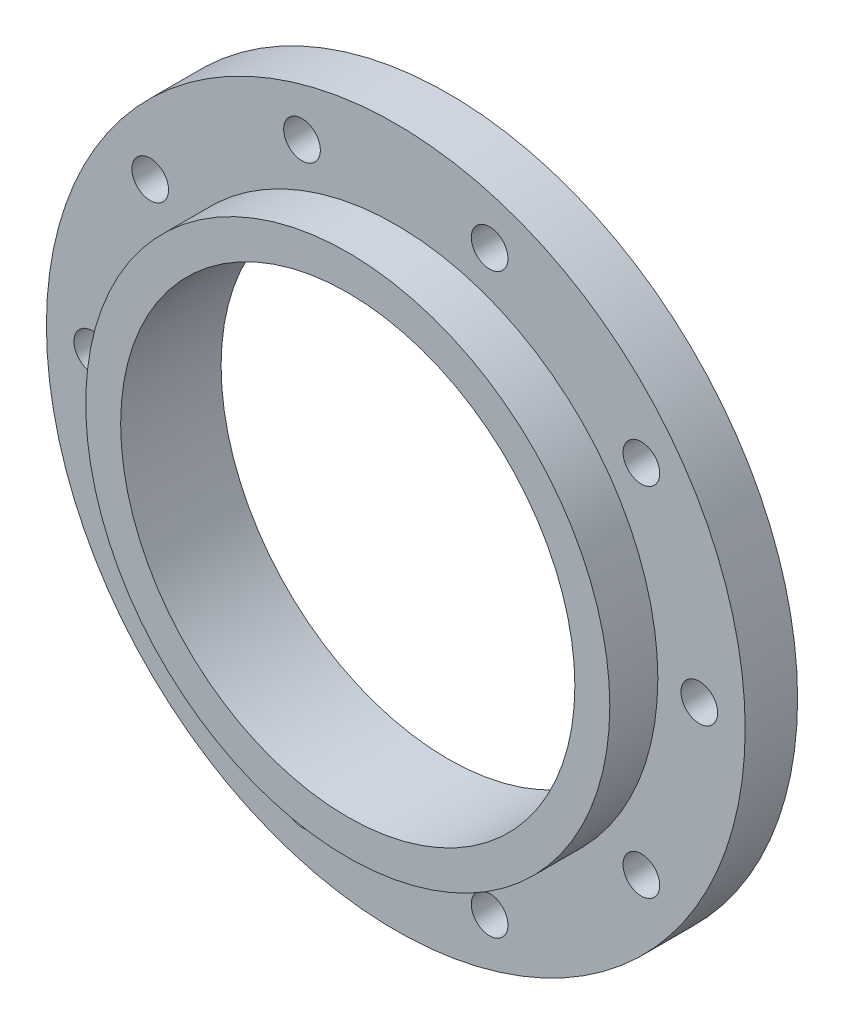
SolidWorks part; units mm, degrees
ref_plane "Front Plane" through (0, 0, 0) normal (0, 0, 1) x (1, 0, 0)
ref_plane "Top Plane" through (0, 0, 0) normal (0, 1, 0) x (1, 0, 0)
ref_plane "Right Plane" through (0, 0, 0) normal (1, 0, 0) x (0, 0, -1)
ref_plane "Plane1" through (0, 0, 0) normal (0, -1, 0) x (1, 0, 0)
sketch "Sketch1" plane through (0, 0, 0) normal (0, -1, 0) x (1, 0, 0)
  line L0 (80, 0) -> (0, 0)
  line L1 (0, 0) -> (0, -12)
  line L2 (0, -12) -> (80, -12)
  line L3 (80, -12) -> (80, 0)
  line L4 (0, 0) -> (0, -12) construction
revolve "Revolve1" add sketch "Sketch1" angle 360 about L4
sketch "Sketch2" plane through (0, 0, 0) normal (0, 0, 1) x (1, 0, 0)
  circle A0 centre (0, 0) radius 60
extrude "Boss-Extrude1" add sketch "Sketch2" along normal blind 11
hole_wizard "Ø8.4 (8.4) Diameter Hole1" positions "Sketch4" profile "Sketch3" hole size "Ø8.4" standard "ANSI Metric"
sketch "Sketch4" plane through (0, 0, -12) normal (0, 0, -1) x (-1, 0, 0)
  point P0 (21.4767, 66.0984)
  point P1 (56.2267, 40.8511)
  point P2 (69.5, 0)
  point P3 (56.2267, -40.8511)
  point P4 (21.4767, -66.0984)
  point P5 (-21.4767, -66.0984)
  point P6 (-56.2267, -40.8511)
  point P7 (-69.5, 0)
  point P8 (-56.2267, 40.8511)
  point P9 (-21.4767, 66.0984)
sketch "Sketch3" plane through (-21.4767, 66.0984, -12) normal (1, 0, 0) x (0, 1, 0)
  line L0 (0, 0) -> (0, 23)
  line L1 (0, 23) -> (4.2, 23)
  line L2 (4.2, 23) -> (4.2, 0)
  line L5 (4.2, 0) -> (0, 0)
  line L11 (0, -6.35) -> (0, 107.95) construction
  dimension "Thru Hole Dia." = 8.4
  dimension "Thru Hole Depth" = 23
hole_wizard "M100 Clearance Hole1" positions "Sketch6" profile "Sketch5" hole size "M100" standard "ANSI Metric"
sketch "Sketch6" plane through (0, 0, -12) normal (0, 0, -1) x (-1, 0, 0)
  point P0 (0, 0)
sketch "Sketch5" plane through (0, 0, -12) normal (1, 0, 0) x (0, 1, 0)
  line L0 (0, 0) -> (0, 23)
  line L1 (0, 23) -> (52, 23)
  line L2 (52, 23) -> (52, 0)
  line L5 (52, 0) -> (0, 0)
  line L11 (0, -6.35) -> (0, 107.95) construction
  dimension "Thru Hole Dia." = 104
  dimension "Thru Hole Depth" = 23
